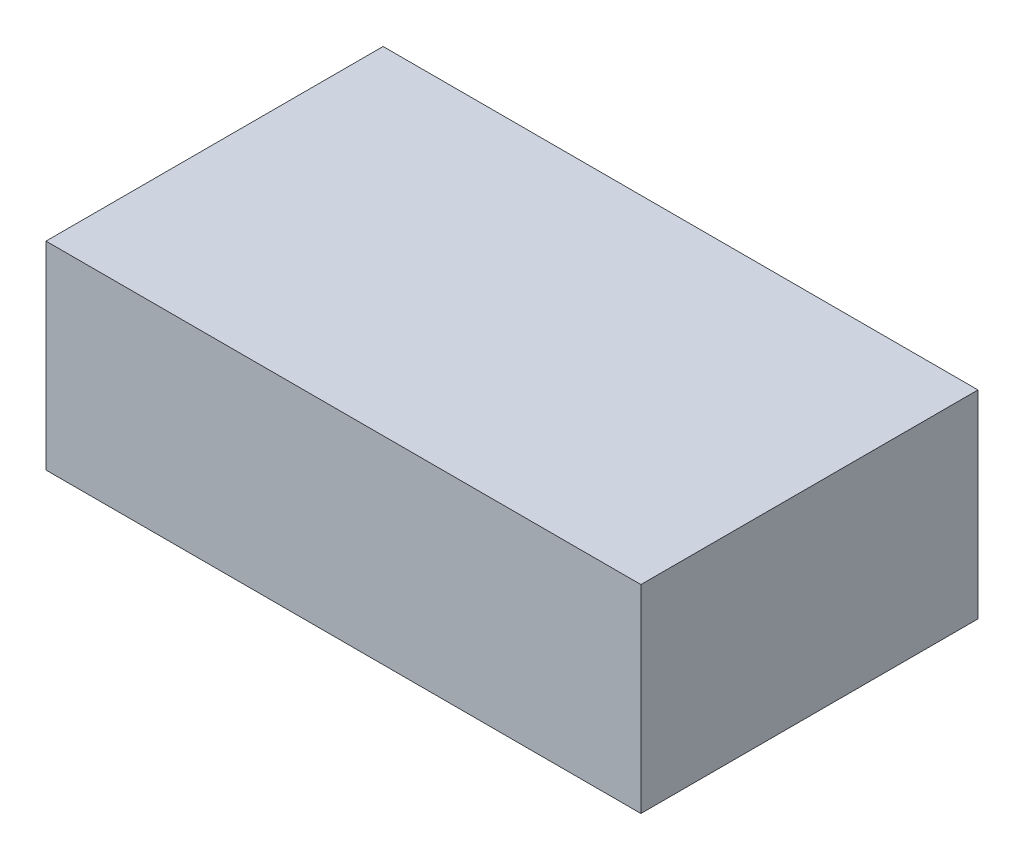
SolidWorks part; units mm, degrees
ref_plane "Front Plane" through (0, 0, 0) normal (0, 0, 1) x (1, 0, 0)
ref_plane "Top Plane" through (0, 0, 0) normal (0, 1, 0) x (1, 0, 0)
ref_plane "Right Plane" through (0, 0, 0) normal (1, 0, 0) x (0, 0, -1)
sketch "Sketch1" plane through (0, 0, 0) normal (0, 1, 0) x (1, 0, 0)
  line L1 (0, 0) -> (381, 0)
  line L2 (0, 0) -> (0, 215.9)
  line L3 (0, 215.9) -> (381, 215.9)
  line L4 (381, 0) -> (381, 215.9)
  dimension "D1" = 381
  dimension "D2" = 215.9
extrude "Boss-Extrude1" add sketch "Sketch1" along normal blind 127
